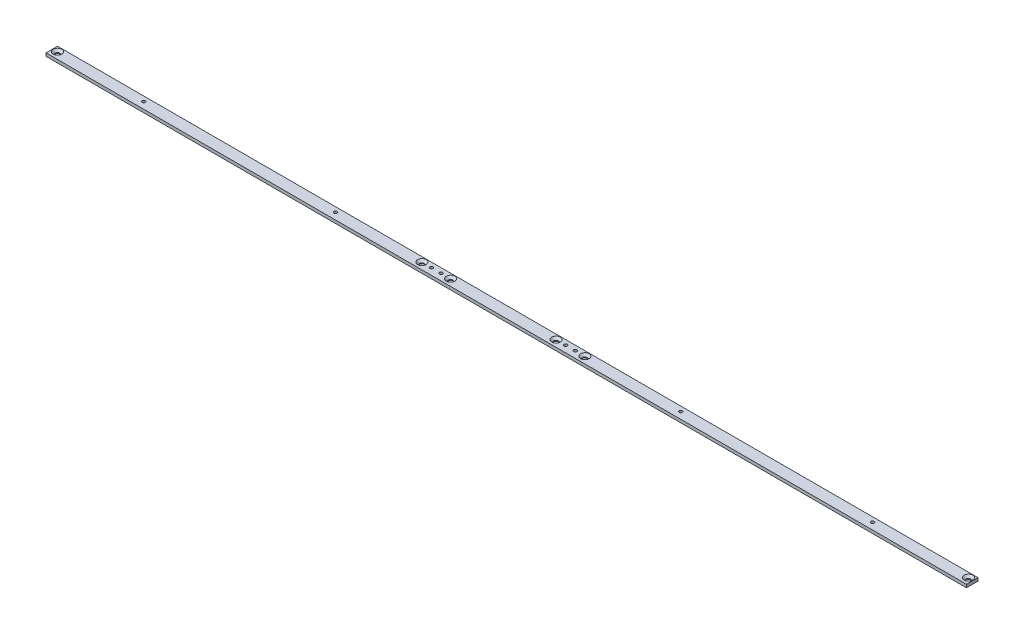
SolidWorks part; units mm, degrees
ref_plane "Front Plane" through (0, 0, 0) normal (0, 0, 1) x (1, 0, 0)
ref_plane "Top Plane" through (0, 0, 0) normal (0, 1, 0) x (1, 0, 0)
ref_plane "Right Plane" through (0, 0, 0) normal (1, 0, 0) x (0, 0, -1)
sketch "Sketch1" plane through (0, 0, 0) normal (0, 1, 0) x (1, 0, 0)
  line L1 (-480, -6) -> (480, -6)
  line L2 (-480, -6) -> (-480, 6)
  line L3 (-480, 6) -> (480, 6)
  line L4 (480, -6) -> (480, 6)
  line L5 (-480, -6) -> (480, 6) construction
  line L6 (-480, 6) -> (480, -6) construction
  point P0 (0, 0)
  dimension "D1" = 960
  dimension "D2" = 12
extrude "Boss-Extrude1" add sketch "Sketch1" along normal blind 3.175
hole_wizard "CSK for M4 SFHCS1" positions "Sketch2" profile "Sketch3" countersink size "M4" standard "ANSI Metric" end condition through all
sketch "Sketch2" plane through (0, 3.175, 0) normal (0, 1, 0) x (1, 0, 0)
  line L2 (-95, 1) -> (-65, 1)
  line L4 (45, 1) -> (75, 1)
  line L5 (480, 6) -> (-480, 6) construction
  line L6 (-480, 6) -> (-480, -6) construction
  point P7 (475, 1)
  point P9 (-95, 1)
  point P10 (-65, 1)
  point P14 (-80, 1)
  point P15 (45, 1)
  point P16 (75, 1)
  point P22 (60, 1)
  point P25 (-475, 1)
  dimension "D1" = 395
  dimension "D2" = 5
  dimension "D3" = 30
  dimension "D4" = 140
  dimension "D5" = 30
  dimension "D6" = 5
  dimension "D7" = 5
  dimension "D8" = 5
sketch "Sketch3" plane through (475, 3.175, -1) normal (1, 0, 0) x (0, 0, 1)
  line L0 (0, 0) -> (0, 3.175)
  line L1 (0, 3.175) -> (2.25, 3.175)
  line L2 (2.25, 3.175) -> (2.25, 2.23)
  line L3 (2.25, 2.23) -> (4.48, 0)
  line L5 (4.48, 0) -> (0, 0)
  line L6 (-2.25, 2.23) -> (-4.48, 0) construction
  line L11 (0, -6.35) -> (0, 107.95) construction
  dimension "Thru Hole Dia." = 4.5
  dimension "Thru Hole Depth" = 3.175
  dimension "Near C'Sink Dia." = 8.96
  dimension "Near C'Sink Angle" = 90
hole_wizard "M4x0.7 Tapped Hole2" positions "Sketch4" profile "Sketch6" tap size "M4x0.7" standard "ANSI Metric" end condition through all
sketch "Sketch4" plane through (0, 3.175, 0) normal (0, 1, 0) x (1, 0, 0)
  line L3 (-85, 1) -> (-75, 1)
  line L5 (480, 6) -> (-480, 6) construction
  line L6 (55, 1) -> (65, 1)
  line L7 (475, 1) -> (75, 1)
  line L9 (175, 1) -> (375, 1)
  line L10 (-385, 1) -> (-185, 1)
  line L11 (-475, 1) -> (-95, 1)
  circle A0 centre (-95, 1) radius 4.48 construction
  circle A1 centre (45, 1) radius 4.48 construction
  point P1 (-85, 1)
  point P2 (-75, 1)
  point P6 (55, 1)
  point P7 (65, 1)
  point P43 (175, 1)
  point P44 (375, 1)
  point P47 (275, 1)
  point P48 (275, 1)
  point P54 (-385, 1)
  point P55 (-185, 1)
  point P69 (-285, 1)
  point P70 (-285, 1)
  dimension "D7" = 200
  dimension "D1" = 10
  dimension "D2" = 10
  dimension "D3" = 10
  dimension "D4" = 10
  dimension "D5" = 5
  dimension "D6" = 5
  dimension "D8" = 200
sketch "Sketch6" plane through (-85, 3.175, -1) normal (1, 0, 0) x (0, 0, 1)
  line L0 (0, 0) -> (0, 3.175)
  line L1 (0, 3.175) -> (1.65, 3.175)
  line L2 (1.65, 3.175) -> (1.65, 0)
  line L5 (1.65, 0) -> (0, 0)
  line L11 (0, -6.35) -> (0, 107.95) construction
  dimension "Thru Tap Drill Dia." = 3.3
  dimension "Thru Tap Drill Depth" = 3.175
cosmetic thread "Hole Thread3"
cosmetic thread "Hole Thread4"
cosmetic thread "Hole Thread5"
cosmetic thread "Hole Thread6"
cosmetic thread "Hole Thread7"
cosmetic thread "Hole Thread8"
cosmetic thread "Hole Thread9"
cosmetic thread "Hole Thread10"
